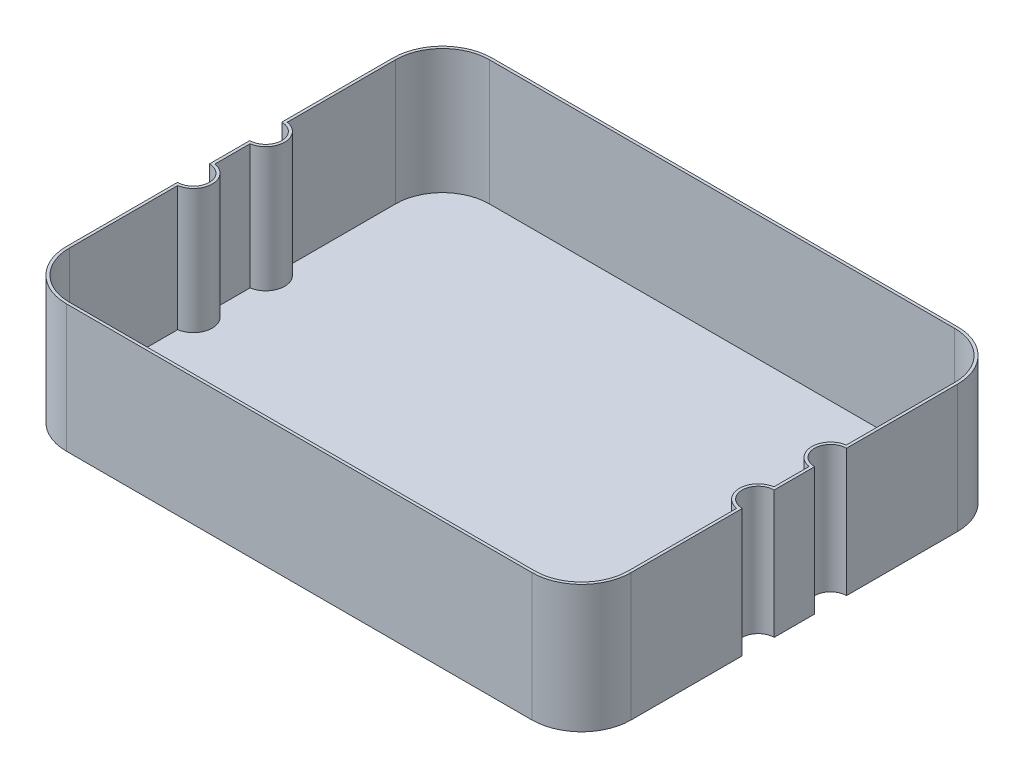
SolidWorks part; units mm, degrees
ref_plane "前视基准面" through (0, 0, 0) normal (0, 0, 1) x (1, 0, 0)
ref_plane "上视基准面" through (0, 0, 0) normal (0, 1, 0) x (1, 0, 0)
ref_plane "右视基准面" through (0, 0, 0) normal (1, 0, 0) x (0, 0, -1)
sketch "草图1" plane through (0, 0, 0) normal (0, 1, 0) x (1, 0, 0)
  line L1 (-199, -150) -> (199, -150)
  line L2 (-199, -150) -> (-199, 150)
  line L3 (-199, 150) -> (199, 150)
  line L4 (199, -150) -> (199, 150)
  line L5 (-199, -150) -> (199, 150) construction
  line L6 (-199, 150) -> (199, -150) construction
  point P0 (0, 0)
  dimension "D1" = 398
  dimension "D2" = 300
extrude "凸台-拉伸1" add sketch "草图1" along normal blind 90
fillet "圆角1" radius 35 4 edges at (-199, 45, 150) (-199, 45, -150) (199, 45, -150) (199, 45, 150)
sketch "草图2" plane through (0, 90, 0) normal (0, 1, 0) x (1, 0, 0)
  line L0 (-199, 0) -> (199, 0) construction
  line L1 (-199, 115) -> (-199, -115) construction
  line L2 (199, -115) -> (199, 115) construction
  line L3 (0, 150) -> (0, -150) construction
  line L4 (164, 150) -> (-164, 150) construction
  line L5 (-164, -150) -> (164, -150) construction
  circle A0 centre (-199, 25.5) radius 11.25
  circle A1 centre (-199, -25.5) radius 11.25
  circle A2 centre (199, -25.5) radius 11.25
  circle A3 centre (199, 25.5) radius 11.25
  dimension "D1" = 22.5
  dimension "D2" = 51
extrude "切除-拉伸1" cut sketch "草图2" against normal blind 90
shell "抽壳1" thickness 2
